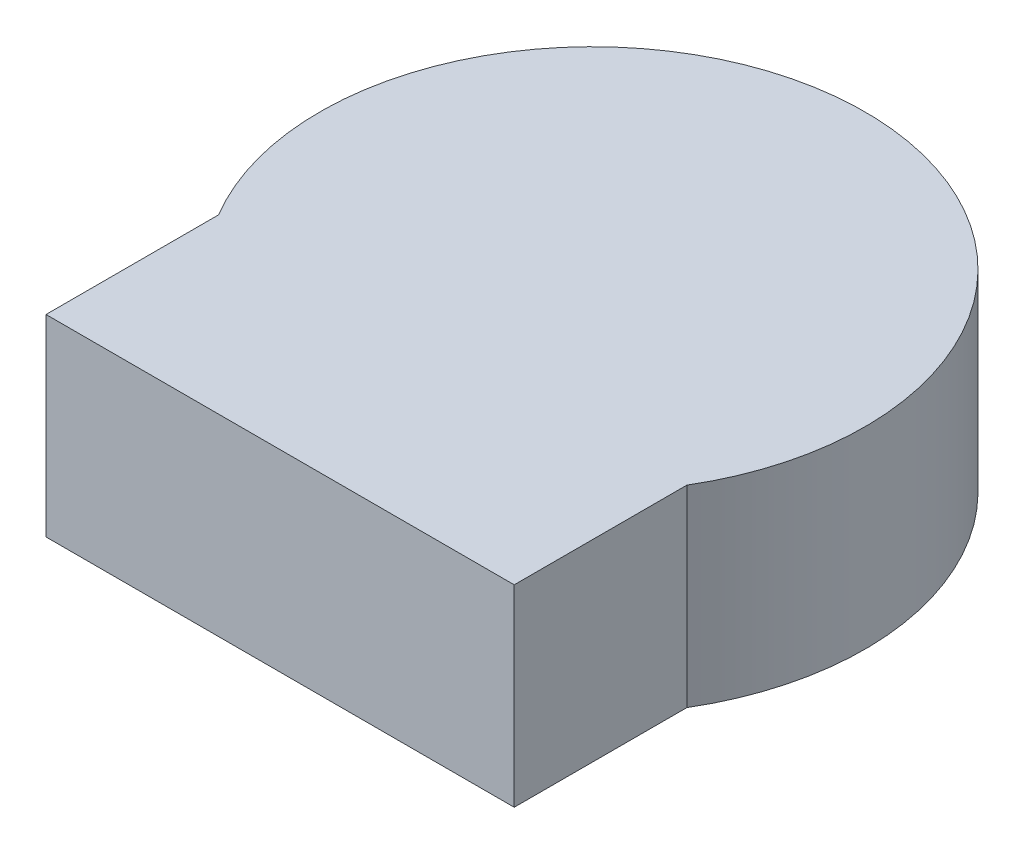
SolidWorks part; units mm, degrees
ref_plane "Front Plane" through (0, 0, 0) normal (0, 0, 1) x (1, 0, 0)
ref_plane "Top Plane" through (0, 0, 0) normal (0, 1, 0) x (1, 0, 0)
ref_plane "Right Plane" through (0, 0, 0) normal (1, 0, 0) x (0, 0, -1)
sketch "Sketch1" plane through (0, 0, 0) normal (0, 1, 0) x (1, 0, 0)
  line L0 (0, -70.75) -> (0, -81.05)
  line L1 (-70.75, 0) -> (-70.75, -81.05)
  line L2 (-70.75, -81.05) -> (-60.75, -81.05)
  line L3 (-60.75, -81.05) -> (-60.75, -36.2629)
  line L4 (-60.75, -36.2629) -> (60.75, -36.2629)
  line L6 (60.75, -36.2629) -> (-60.75, -36.2629)
  line L7 (60.75, -36.2629) -> (60.75, -81.05)
  line L8 (60.75, -81.05) -> (-60.75, -81.05)
  line L9 (-60.75, -36.2629) -> (-60.75, -81.05)
  circle A0 centre (0, 0) radius 70.75
  dimension "D1" = 141.5
  dimension "D2" = 10.3
  dimension "D3" = 10
extrude "Boss-Extrude1" add sketch "Sketch1" along normal blind 50 contours A0 L3 L8 L0 | A0 L0 L8 L7
sketch "Sketch2" plane through (0, 0, 0) normal (0, -1, 0) x (-1, 0, 0)
  circle A0 centre (0, 0) radius 50
  circle A1 centre (0, 50) radius 1.5
  circle A2 centre (0, 0) radius 2.55
  dimension "D1" = 100
  dimension "D2" = 3
  dimension "D3" = 5.1
extrude "Cut-Extrude1" cut sketch "Sketch2" against normal blind 5 contours A1 | A2
pattern_circular "CirPattern1" count 3 over 360 about axis through (0, 0, 0) along (0, 1, 0) of "Cut-Extrude1"
ref_plane "Plane1" through (0, 0, 46.05) normal (0, 0, 1) x (1, 0, 0)
